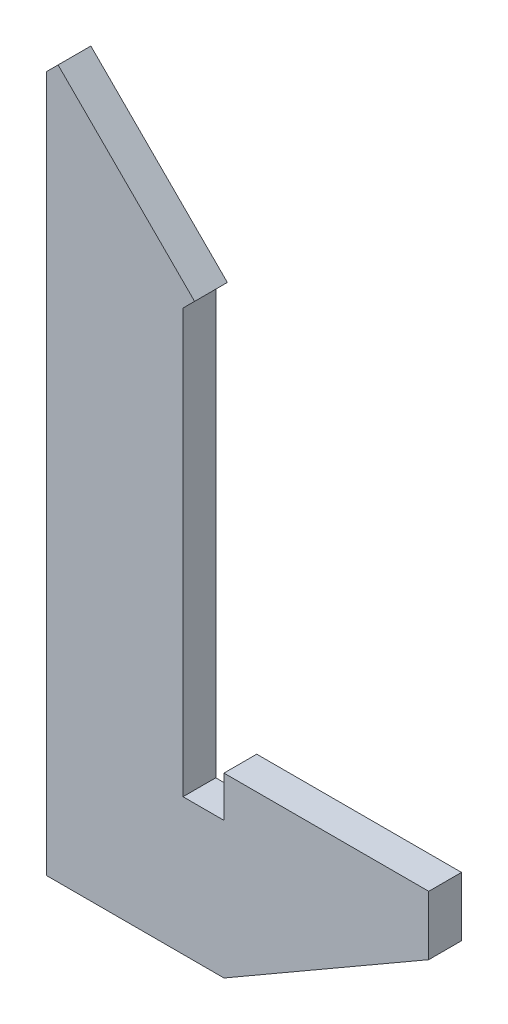
SolidWorks part; units mm, degrees
material "PBT General Purpose"
ref_plane "Front Plane" through (0, 0, 0) normal (0, 0, 1) x (1, 0, 0)
ref_plane "Top Plane" through (0, 0, 0) normal (0, 1, 0) x (1, 0, 0)
ref_plane "Right Plane" through (0, 0, 0) normal (1, 0, 0) x (0, 0, -1)
sketch "Sketch1" plane through (0, 0, 0) normal (0, 0, 1) x (1, 0, 0)
  line L0 (0, 0) -> (-1.5, 0)
  line L1 (-1.5, 0) -> (-1.5, -0.3)
  line L2 (-1.5, -0.3) -> (-1.8, -0.3)
  line L3 (-1.8, -0.3) -> (-1.8, 2.8)
  line L5 (-2.8, 3.8) -> (-2.8, -1.3)
  line L6 (-2.8, -1.3) -> (-1.5, -1.3)
  line L7 (-1.5, -1.3) -> (0, -0.434)
  line L8 (0, -0.434) -> (0, 0)
  line L9 (-1.8, 2.8) -> (-2.8, 3.8) construction
  line L10 (0, 0) -> (1, 0) construction
  line L11 (-1.8, 2.8) -> (1, 0) construction
  line L12 (-1.8, 2.8) -> (-1.7151, 2.8849)
  line L13 (-1.7151, 2.8849) -> (-2.7151, 3.8849)
  line L14 (-2.7151, 3.8849) -> (-2.8, 3.8)
  point P11 (-1.65, -0.3)
  dimension "D1" = 1.5
  dimension "D2" = 0.3
  dimension "D3" = 0.3
  dimension "D4" = 1
  dimension "D5" = 45
  dimension "D6" = 120
  dimension "D7" = 1
  dimension "D8" = 1
  dimension "D9" = 45
  dimension "D10" = 0.12
extrude "Boss-Extrude1" add sketch "Sketch1" along normal mid plane 0.24 contours L5 L6 L7 L8 L0 L1 L2 L3 L12 L13 L14
